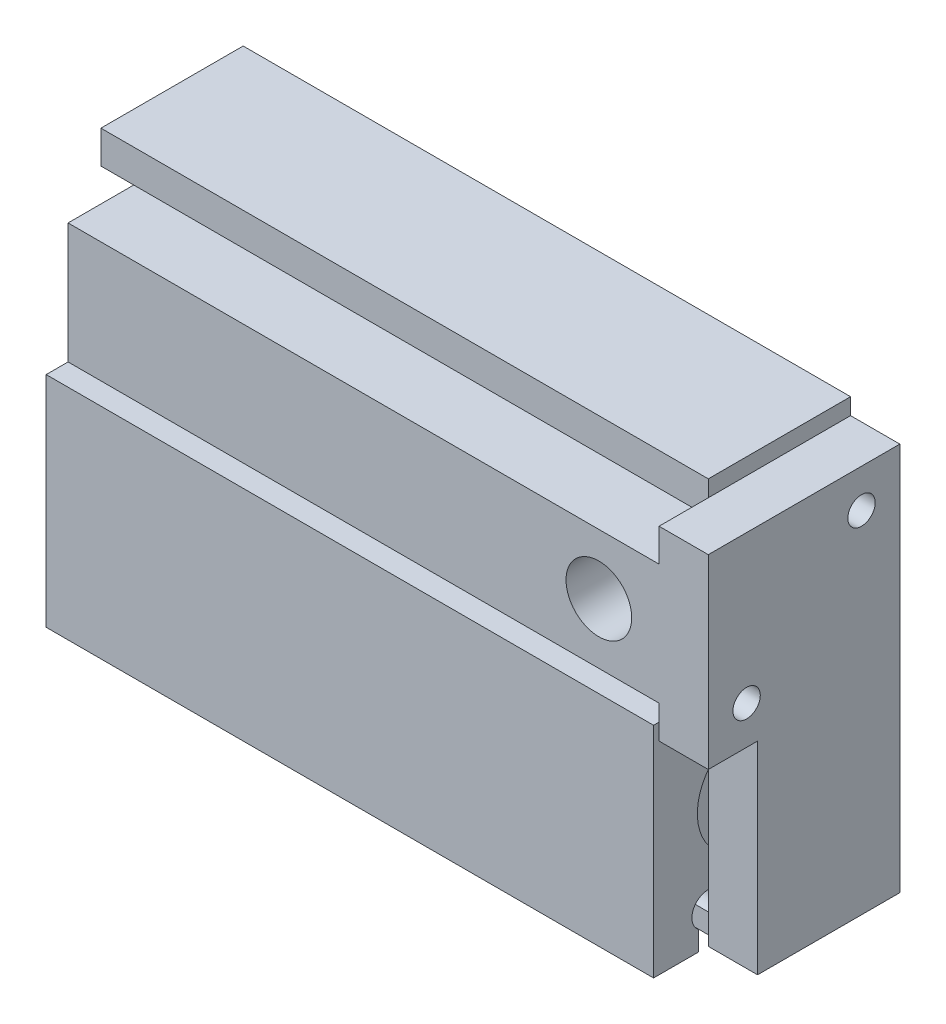
SolidWorks part; units mm, degrees
ref_plane "前视基准面" through (0, 0, 0) normal (0, 0, 1) x (1, 0, 0)
ref_plane "上视基准面" through (0, 0, 0) normal (0, 1, 0) x (1, 0, 0)
ref_plane "右视基准面" through (0, 0, 0) normal (1, 0, 0) x (0, 0, -1)
sketch "草图1" plane through (0, 0, 0) normal (1, 0, 0) x (0, 0, -1)
  line L1 (0, 0) -> (18, 0)
  line L2 (0, 0) -> (0, 37)
  line L3 (0, 37) -> (18, 37)
  line L4 (18, 0) -> (18, 37)
  dimension "D1" = 18
  dimension "D2" = 37
extrude "凸台-拉伸1" add sketch "草图1" along normal blind 55.5
sketch "草图2" plane through (0, 0, 0) normal (-1, 0, 0) x (0, 0, 1)
  line L0 (-9, 0) -> (-9, 18.5569) construction
  line L1 (0, 0) -> (-18, 0) construction
  circle A0 centre (-9, 11) radius 5
  dimension "D1" = 10
  dimension "D2" = 11
extrude "切除-拉伸1" cut sketch "草图2" against normal blind 0.5
sketch "草图3" plane through (55.5, 0, 0) normal (1, 0, 0) x (0, 0, -1)
  line L0 (9, 0) -> (9, 21.4556) construction
  line L1 (0, 0) -> (18, 0) construction
  circle A0 centre (9, 11) radius 5
  dimension "D1" = 10
  dimension "D2" = 11
extrude "切除-拉伸2" cut sketch "草图3" against normal blind 0.5
sketch "草图4" plane through (0, 0, 0) normal (-1, 0, 0) x (0, 0, 1)
  line L0 (-9, 0) -> (-9, 5.0998) construction
  line L1 (0, 0) -> (-18, 0) construction
  circle A0 centre (-13, 3) radius 1.5
  circle A1 centre (-5, 3) radius 1.5
  dimension "D1" = 3
  dimension "D2" = 8
  dimension "D3" = 3
extrude "切除-拉伸3" cut sketch "草图4" against normal through all
sketch "草图5" plane through (0, 0, 0) normal (-1, 0, 0) x (0, 0, 1)
  line L1 (0, 0) -> (-18, 0) construction
  line L2 (-13.9177, 0) -> (-12.0823, 0)
  line L3 (-13.9177, 0) -> (-13.9177, 2.7565)
  line L4 (-13.9177, 2.7565) -> (-12.0823, 2.7565)
  line L5 (-12.0823, 0) -> (-12.0823, 2.7565)
  line L6 (-9, 0) -> (-9, 3.3444) construction
  line L7 (-5.9177, 0) -> (-5.9177, 2.7565)
  line L8 (-4.0823, 2.7565) -> (-5.9177, 2.7565)
  line L9 (-4.0823, 0) -> (-4.0823, 2.7565)
  line L10 (-4.0823, 0) -> (-5.9177, 0)
  line L11 (-13, 2.7565) -> (-13, 0) construction
  line L12 (-5, 2.7565) -> (-5, 0) construction
  dimension "D1" = 8
extrude "切除-拉伸4" cut sketch "草图5" against normal through all
sketch "草图6" plane through (0, 0, 0) normal (-1, 0, 0) x (0, 0, 1)
  line L1 (0, 37) -> (-5, 37)
  line L2 (0, 37) -> (0, 20)
  line L3 (0, 20) -> (-5, 20)
  line L4 (-5, 37) -> (-5, 20)
  dimension "D1" = 5
  dimension "D2" = 17
extrude "切除-拉伸5" cut sketch "草图6" against normal through all
sketch "草图7" plane through (0, 0, 0) normal (-1, 0, 0) x (0, 0, 1)
  line L0 (-5, 37) -> (-5, 20) construction
  line L1 (-5, 34) -> (-13, 34)
  line L2 (-5, 34) -> (-5, 22)
  line L3 (-5, 22) -> (-13, 22)
  line L4 (-13, 34) -> (-13, 22)
  line L5 (-5, 28) -> (-13, 28) construction
  circle A0 centre (-9, 11) radius 5 construction
  dimension "D1" = 17
  dimension "D2" = 12
  dimension "D3" = 8
extrude "切除-拉伸6" cut sketch "草图7" against normal through all
sketch "草图8" plane through (55, 0, 0) normal (1, 0, 0) x (0, 0, -1)
  circle A0 centre (9, 11) radius 2.5
  dimension "D1" = 5
extrude "凸台-拉伸2" add sketch "草图8" along normal blind 1.5
sketch "草图9" plane through (56.5, 0, 0) normal (1, 0, 0) x (0, 0, -1)
  line L0 (18, 0) -> (18, 37) construction
  line L1 (17, 36.5) -> (-0.5, 36.5)
  line L2 (17, 36.5) -> (17, 1)
  line L3 (17, 1) -> (-0.5, 1)
  line L4 (-0.5, 36.5) -> (-0.5, 1)
  line L5 (18, 37) -> (5, 37) construction
  dimension "D1" = 1
  dimension "D2" = 0.5
  dimension "D3" = 35.5
  dimension "D4" = 17.5
extrude "凸台-拉伸3" add sketch "草图9" along normal blind 4.5
sketch "草图10" plane through (56.5, 0, 0) normal (-1, 0, 0) x (0, 0, 1)
  line L0 (0.5, 36.5) -> (0.5, 1) construction
  line L1 (-6.5, 33.5) -> (0.5, 33.5)
  line L2 (-6.5, 33.5) -> (-6.5, 22.5)
  line L3 (-6.5, 22.5) -> (0.5, 22.5)
  line L4 (0.5, 33.5) -> (0.5, 22.5)
  line L5 (-5, 34) -> (-13, 34) construction
  line L6 (-13, 22) -> (-5, 22) construction
  dimension "D1" = 0.5
  dimension "D2" = 0.5
  dimension "D3" = 7
extrude "凸台-拉伸4" add sketch "草图10" along normal blind 54
sketch "草图11" plane through (61, 0, 0) normal (1, 0, 0) x (0, 0, -1)
  line L0 (-0.5, 36.5) -> (-0.5, 1) construction
  line L1 (-0.5, 19.5) -> (4, 19.5)
  line L2 (-0.5, 19.5) -> (-0.5, 1)
  line L3 (-0.5, 1) -> (4, 1)
  line L4 (4, 19.5) -> (4, 1)
  line L5 (-0.5, 1) -> (17, 1) construction
  line L6 (17, 36.5) -> (-0.5, 36.5) construction
  dimension "D1" = 17
  dimension "D2" = 4.5
extrude "切除-拉伸7" cut sketch "草图11" against normal up to next
hole_wizard "M3 螺纹孔1" positions "草图13" profile "草图12" tap size "M3" standard "ISO"
sketch "草图13" plane through (61, 0, 0) normal (1, 0, 0) x (0, 0, -1)
  line L0 (18, 0) -> (18, 37) construction
  line L1 (18, 37) -> (5, 37) construction
  point P0 (13.5, 33)
  point P1 (3, 23)
  dimension "D1" = 4.5
  dimension "D2" = 4
  dimension "D3" = 10.5
  dimension "D4" = 10
sketch "草图12" plane through (61, 33, -13.5) normal (0, 1, 0) x (0, 0, -1)
  line L0 (0, 0) -> (0, 8.2511)
  line L1 (0, 8.2511) -> (1.25, 7.5)
  line L2 (1.25, 7.5) -> (1.25, 0)
  line L5 (1.25, 0) -> (0, 0)
  line L10 (0, 8.2511) -> (-1.25, 7.5) construction
  line L11 (0, -6.35) -> (0, 107.95) construction
  dimension "螺纹孔钻头直径" = 2.5
  dimension "螺纹孔钻头深度" = 7.5
  dimension "导头角度" = 118
cosmetic thread "孔螺蚊线1" parameters "D1"=6, "D2"=3
cosmetic thread "孔螺蚊线2" parameters "D1"=6, "D2"=3
hole_wizard "M3 六角凹头螺钉的柱形沉头孔1" positions "草图15" profile "草图14" counterbore size "M3" standard "ISO"
sketch "草图15" plane through (0, 0, -13) normal (0, 0, 1) x (1, 0, 0)
  line L0 (0, 28) -> (56.5837, 28) construction
  line L1 (0, 34) -> (0, 22) construction
  line L2 (55.5, 31.8544) -> (55.5, 22) construction
  point P0 (4, 28)
  point P2 (51.5, 28)
  dimension "D1" = 4
  dimension "D2" = 4
sketch "草图14" plane through (4, 28, -13) normal (1, 0, 0) x (0, -1, 0)
  line L0 (0, 0) -> (0, 5)
  line L1 (0, 5) -> (1.7, 5)
  line L3 (1.7, 5) -> (1.7, 3)
  line L4 (1.7, 3) -> (3.25, 3)
  line L5 (3.25, 3) -> (3.25, 0)
  line L7 (3.25, 0) -> (0, 0)
  line L11 (0, -6.35) -> (0, 107.95) construction
  dimension "通孔孔直径" = 3.4
  dimension "通孔孔深度" = 5
  dimension "柱形沉头孔直径" = 6.5
  dimension "柱形沉头孔深度" = 3
sketch "草图16" plane through (0, 0, 0.5) normal (0, 0, 1) x (1, 0, 0)
  line L0 (2.5, 28) -> (53.798, 28) construction
  line L1 (2.5, 22.5) -> (2.5, 33.5) construction
  line L2 (61, 36.5) -> (61, 19.5) construction
  circle A0 centre (51, 28) radius 3
  dimension "D1" = 6
  dimension "D2" = 10
extrude "切除-拉伸8" cut sketch "草图16" against normal up to next
